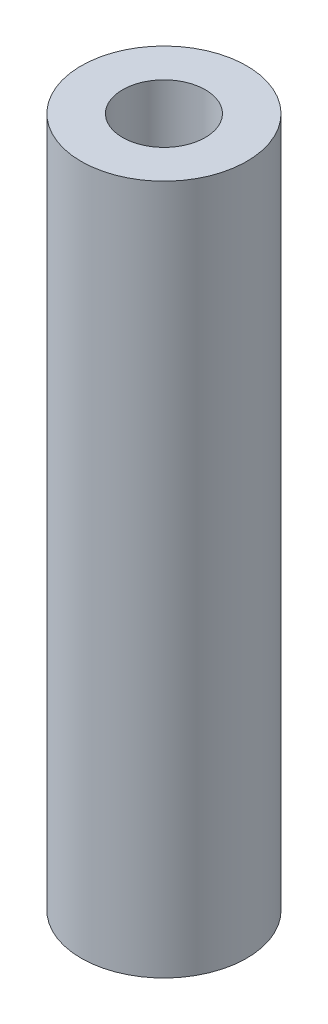
SolidWorks part; units mm, degrees
ref_plane "前视基准面" through (0, 0, 0) normal (0, 0, 1) x (1, 0, 0)
ref_plane "上视基准面" through (0, 0, 0) normal (0, 1, 0) x (1, 0, 0)
ref_plane "右视基准面" through (0, 0, 0) normal (1, 0, 0) x (0, 0, -1)
sketch "Sketch1" plane through (0, 0, 0) normal (0, 1, 0) x (1, 0, 0)
  circle A0 centre (0, 0) radius 1.5
  circle A1 centre (0, 0) radius 3
extrude "Boss-Extrude1" add sketch "Sketch1" along normal blind 25
